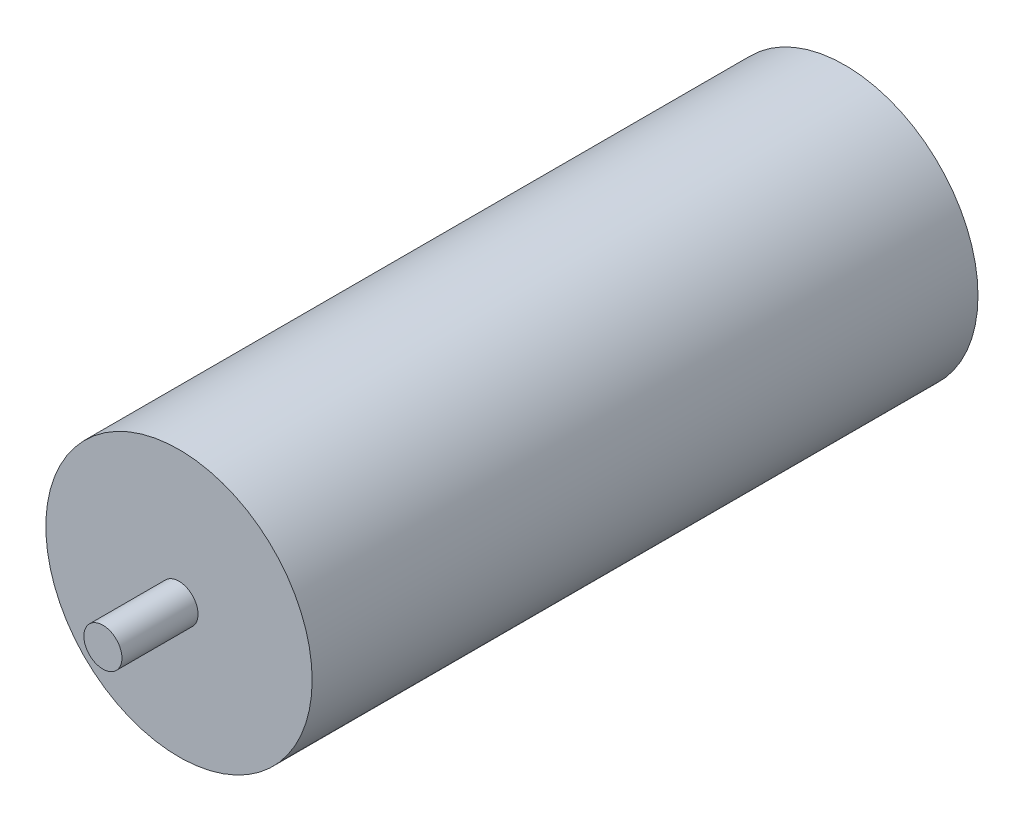
SolidWorks part; units mm, degrees
ref_plane "Front Plane" through (0, 0, 0) normal (0, 0, 1) x (1, 0, 0)
ref_plane "Top Plane" through (0, 0, 0) normal (0, 1, 0) x (1, 0, 0)
ref_plane "Right Plane" through (0, 0, 0) normal (1, 0, 0) x (0, 0, -1)
sketch "Sketch1" plane through (0, 0, 0) normal (0, 0, 1) x (1, 0, 0)
  circle A0 centre (0, 0) radius 35
  dimension "D1" = 70
extrude "Boss-Extrude1" add sketch "Sketch1" along normal mid plane 175
sketch "Sketch2" plane through (0, 0, 87.5) normal (0, 0, 1) x (1, 0, 0)
  circle A0 centre (0, 0) radius 5
  dimension "D1" = 10
extrude "Boss-Extrude2" add sketch "Sketch2" along normal blind 20
mirror "Mirror1" about plane through (0, 0, 0) normal (0, 0, 1) of "Boss-Extrude2"
